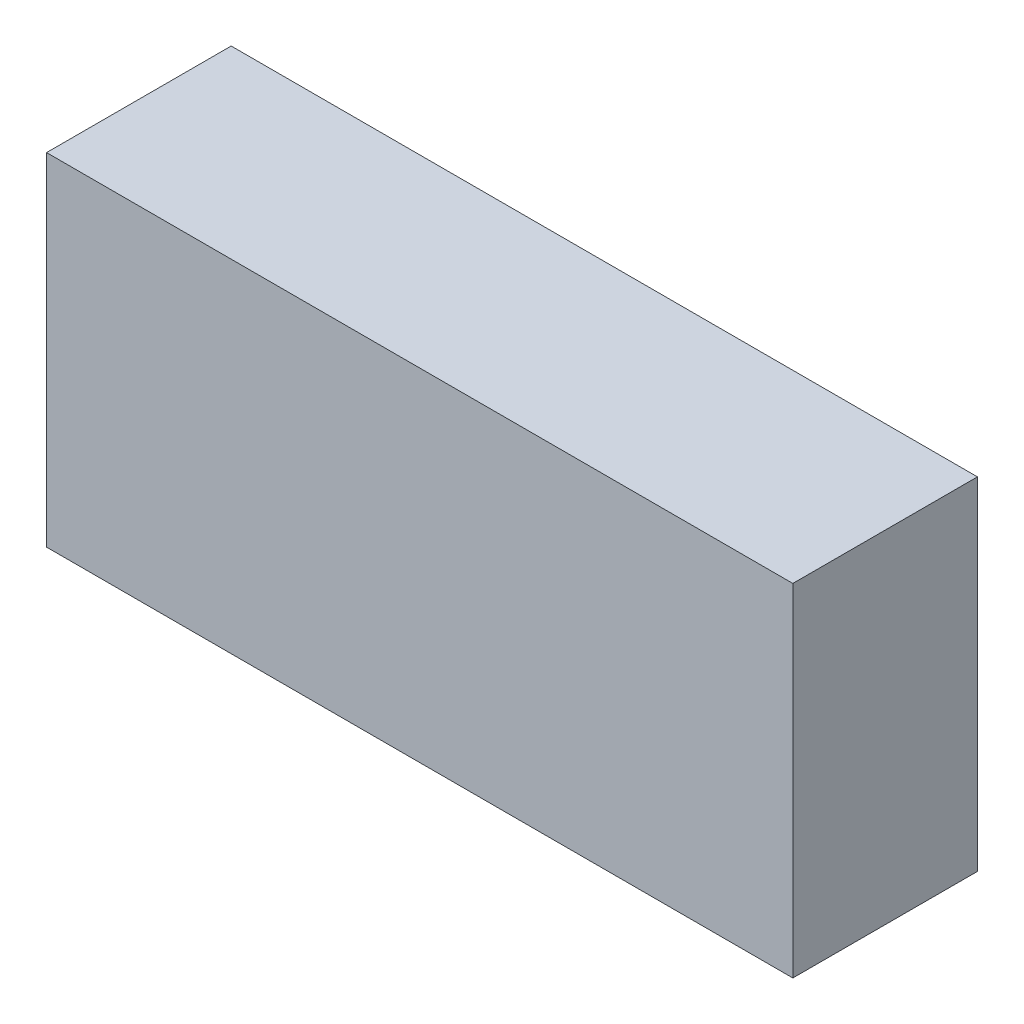
SolidWorks part; units mm, degrees
ref_plane "Front Plane" through (0, 0, 0) normal (0, 0, 1) x (1, 0, 0)
ref_plane "Top Plane" through (0, 0, 0) normal (0, 1, 0) x (1, 0, 0)
ref_plane "Right Plane" through (0, 0, 0) normal (1, 0, 0) x (0, 0, -1)
sketch "Sketch1" plane through (0, 0, 0) normal (0, 1, 0) x (1, 0, 0)
  line L1 (-47.5, 11.75) -> (47.5, 11.75)
  line L2 (-47.5, 11.75) -> (-47.5, -11.75)
  line L3 (-47.5, -11.75) -> (47.5, -11.75)
  line L4 (47.5, 11.75) -> (47.5, -11.75)
  line L5 (-47.5, 11.75) -> (47.5, -11.75) construction
  line L6 (-47.5, -11.75) -> (47.5, 11.75) construction
  point P0 (0, 0)
  dimension "D1" = 95
  dimension "D2" = 23.5
extrude "Boss-Extrude1" add sketch "Sketch1" along normal blind 43.5
